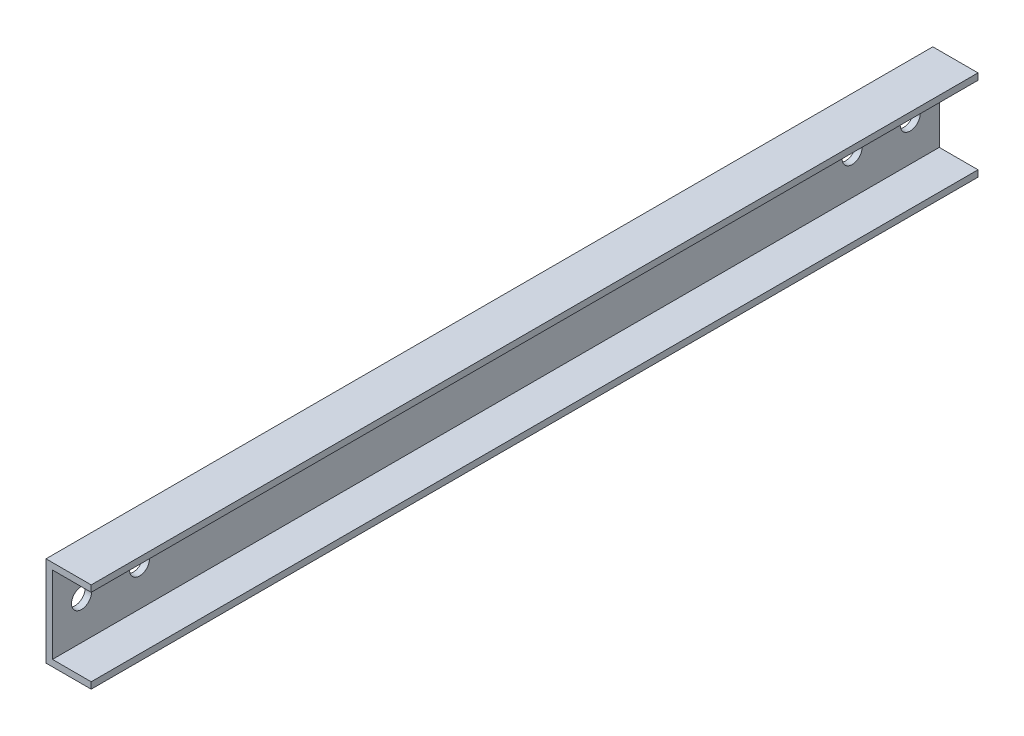
SolidWorks part; units mm, degrees
ref_plane "前视基准面" through (0, 0, 0) normal (0, 0, 1) x (1, 0, 0)
ref_plane "上视基准面" through (0, 0, 0) normal (0, 1, 0) x (1, 0, 0)
ref_plane "右视基准面" through (0, 0, 0) normal (1, 0, 0) x (0, 0, -1)
sketch "草图1" plane through (0, 0, 0) normal (0, 0, 1) x (1, 0, 0)
  line L0 (0, 0) -> (-60, 0)
  line L1 (-60, 0) -> (-60, 120)
  line L2 (-60, 120) -> (0, 120)
  line L3 (0, 130) -> (0, 120)
  line L4 (0, 130) -> (-70, 130)
  line L5 (-70, 130) -> (-70, -10)
  line L6 (-70, -10) -> (0, -10)
  line L7 (0, -10) -> (0, 0)
  dimension "D1" = 140
  dimension "D2" = 120
  dimension "D3" = 10
  dimension "D4" = 10
  dimension "D5" = 70
  dimension "D6" = 70
extrude "拉伸3" add sketch "草图1" along normal blind 1374
sketch "草图10" plane through (-60, 0, 0) normal (1, 0, 0) x (0, 0, -1)
  line L0 (-1374, -10) -> (0, -10) construction
  line L1 (-687, -870) -> (-687, 49130) construction
  line L3 (0, 130) -> (0, -10) construction
  line L4 (0, 0) -> (0, 120) construction
  circle A0 centre (-45, 60) radius 15.5
  circle A1 centre (-135, 60) radius 15.5
  circle A2 centre (-1239, 60) radius 15.5
  circle A3 centre (-1329, 60) radius 15.5
  dimension "D1" = 31
  dimension "D4" = 31
  dimension "D6" = 70
  dimension "D2" = 70
  dimension "D3" = 45
  dimension "D5" = 90
  dimension "D7" = 687
extrude "拉伸11" cut sketch "草图10" against normal through all
